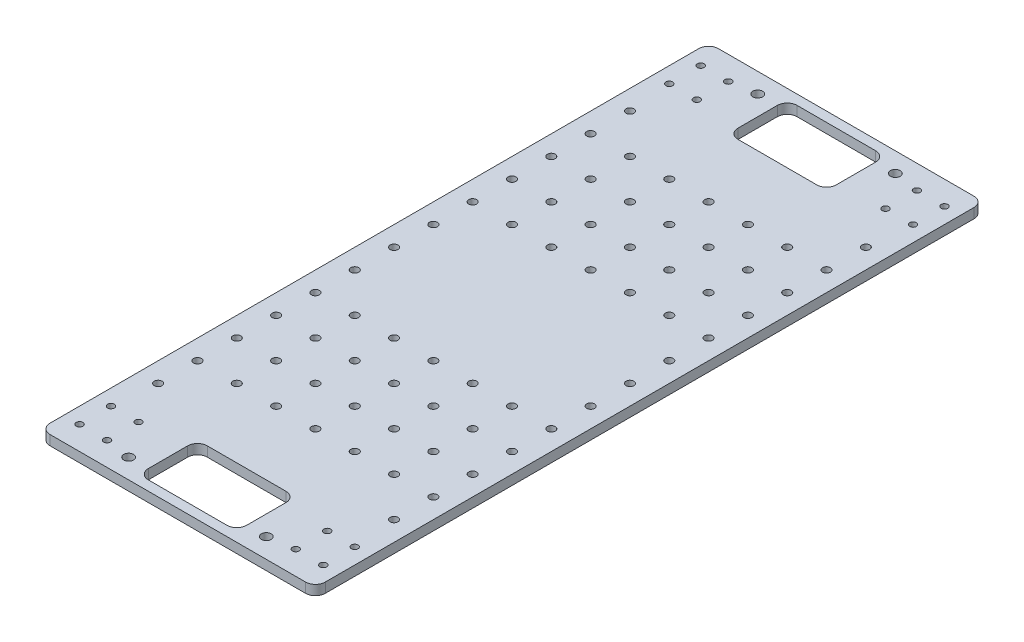
SolidWorks part; units mm, degrees
ref_plane "前视基准面" through (0, 0, 0) normal (0, 0, 1) x (1, 0, 0)
ref_plane "上视基准面" through (0, 0, 0) normal (0, 1, 0) x (1, 0, 0)
ref_plane "右视基准面" through (0, 0, 0) normal (1, 0, 0) x (0, 0, -1)
other "Configuration Table"
sketch "草图1" plane through (0, 0, 0) normal (0, 1, 0) x (1, 0, 0)
  line L0 (-1000, 0) -> (49000, 0)
  line L5 (-100, -170) -> (100, 170) construction
  line L6 (-100, 170) -> (100, -170) construction
  line L11 (0, -1000) -> (0, 49000) construction
  line L12 (-70, 0) -> (-60, 0)
  line L13 (-65, -170) -> (65, -170)
  line L14 (-70, 137) -> (-70, 130)
  line L15 (-70, 163) -> (-40, 163)
  line L16 (-40, 163) -> (-40, 137)
  line L17 (-40, 137) -> (-70, 137)
  line L18 (-70, -165) -> (-70, 165)
  line L19 (-70, 137) -> (-70, 142)
  line L20 (-40, 137) -> (-48, 137)
  line L21 (-48, 137) -> (-48, 142)
  line L22 (-48, 142) -> (-40, 142)
  line L23 (-70, 142) -> (-62, 142)
  line L24 (-62, 142) -> (-62, 137)
  line L25 (-70, 150) -> (-40, 150) construction
  line L28 (-70, 130) -> (0, 130)
  line L29 (-65, 170) -> (65, 170)
  line L30 (70, 165) -> (70, 130)
  line L31 (70, -165) -> (70, 170)
  line L32 (70, -170) -> (70, -130)
  line L33 (-70, -170) -> (-70, -130)
  line L34 (-20, 165) -> (20, 165)
  line L35 (0, 170) -> (0, 150)
  line L36 (-25, 160) -> (-25, 140)
  line L37 (-25, 150) -> (-25, 165)
  line L38 (-25, 150) -> (-25, 135)
  line L43 (25, 150) -> (25, 140)
  line L46 (25, 150) -> (25, 160)
  line L48 (25, -150) -> (25, -140)
  line L49 (25, -150) -> (25, -160)
  line L52 (-25, -150) -> (-25, -160)
  line L53 (-25, -150) -> (-25, -140)
  line L58 (0, 170) -> (0, 150)
  line L59 (0, 170) -> (0, 160)
  line L60 (-20, 135) -> (20, 135)
  line L61 (25, 165) -> (25, 135)
  line L62 (-20, -135) -> (20, -135)
  line L63 (-25, -135) -> (-25, -165)
  line L64 (-20, -165) -> (20, -165)
  line L65 (25, -135) -> (25, -165)
  circle A0 centre (-62, 142) radius 1.7
  circle A1 centre (-48, 142) radius 1.7
  circle A2 centre (-48, 158) radius 1.7
  circle A3 centre (-62, 158) radius 1.7
  circle A4 centre (48, 158) radius 1.7
  circle A5 centre (48, 142) radius 1.7
  circle A6 centre (62, 142) radius 1.7
  circle A7 centre (62, 158) radius 1.7
  circle A8 centre (62, -158) radius 1.7
  circle A9 centre (62, -142) radius 1.7
  circle A10 centre (48, -142) radius 1.7
  circle A11 centre (48, -158) radius 1.7
  circle A12 centre (-48, -142) radius 1.7
  circle A13 centre (-62, -142) radius 1.7
  circle A14 centre (-48, -158) radius 1.7
  circle A15 centre (-62, -158) radius 1.7
  circle A23 centre (35, 160) radius 2.5
  circle A24 centre (-60, 0) radius 2
  circle A27 centre (-60, 20) radius 2
  circle A28 centre (-40, 40) radius 2
  circle A29 centre (-60, 40) radius 2
  circle A30 centre (-40, 60) radius 2
  circle A31 centre (-60, 60) radius 2
  circle A32 centre (-40, 80) radius 2
  circle A33 centre (-60, 80) radius 2
  circle A34 centre (-40, 100) radius 2
  circle A35 centre (-60, 100) radius 2
  circle A37 centre (-60, 120) radius 2
  circle A40 centre (-20, 40) radius 2
  circle A41 centre (-40, 40) radius 2
  circle A42 centre (-20, 60) radius 2
  circle A43 centre (-40, 60) radius 2
  circle A44 centre (-20, 80) radius 2
  circle A45 centre (-40, 80) radius 2
  circle A46 centre (-20, 100) radius 2
  circle A47 centre (-40, 100) radius 2
  circle A52 centre (0, 40) radius 2
  circle A53 centre (-20, 40) radius 2
  circle A54 centre (0, 60) radius 2
  circle A55 centre (-20, 60) radius 2
  circle A56 centre (0, 80) radius 2
  circle A57 centre (-20, 80) radius 2
  circle A58 centre (0, 100) radius 2
  circle A59 centre (-20, 100) radius 2
  circle A64 centre (20, 40) radius 2
  circle A65 centre (0, 40) radius 2
  circle A66 centre (20, 60) radius 2
  circle A67 centre (0, 60) radius 2
  circle A68 centre (20, 80) radius 2
  circle A69 centre (0, 80) radius 2
  circle A70 centre (20, 100) radius 2
  circle A71 centre (0, 100) radius 2
  circle A76 centre (40, 40) radius 2
  circle A77 centre (20, 40) radius 2
  circle A78 centre (40, 60) radius 2
  circle A79 centre (20, 60) radius 2
  circle A80 centre (40, 80) radius 2
  circle A81 centre (20, 80) radius 2
  circle A82 centre (40, 100) radius 2
  circle A83 centre (20, 100) radius 2
  circle A86 centre (60, 20) radius 2
  circle A88 centre (60, 40) radius 2
  circle A89 centre (40, 40) radius 2
  circle A90 centre (60, 60) radius 2
  circle A91 centre (40, 60) radius 2
  circle A92 centre (60, 80) radius 2
  circle A93 centre (40, 80) radius 2
  circle A94 centre (60, 100) radius 2
  circle A95 centre (40, 100) radius 2
  circle A96 centre (60, 120) radius 2
  circle A98 centre (-35, 160) radius 2.5
  circle A99 centre (-40, 120) radius 2 [skipped]
  circle A100 centre (-20, 120) radius 2 [skipped]
  circle A101 centre (0, 120) radius 2 [skipped]
  circle A102 centre (20, 120) radius 2 [skipped]
  circle A103 centre (40, 120) radius 2 [skipped]
  circle A104 centre (-40, 20) radius 2 [skipped]
  circle A105 centre (-20, 20) radius 2 [skipped]
  circle A106 centre (0, 20) radius 2 [skipped]
  circle A107 centre (20, 20) radius 2 [skipped]
  circle A108 centre (40, 20) radius 2 [skipped]
  circle A109 centre (60, 0) radius 2
  circle A110 centre (60, -120) radius 2
  circle A111 centre (40, -100) radius 2
  circle A112 centre (60, -100) radius 2
  circle A113 centre (40, -80) radius 2
  circle A114 centre (60, -80) radius 2
  circle A115 centre (40, -60) radius 2
  circle A116 centre (60, -60) radius 2
  circle A117 centre (40, -40) radius 2
  circle A118 centre (60, -40) radius 2
  circle A119 centre (60, -20) radius 2
  circle A120 centre (20, -100) radius 2
  circle A121 centre (40, -100) radius 2
  circle A122 centre (20, -80) radius 2
  circle A123 centre (40, -80) radius 2
  circle A124 centre (20, -60) radius 2
  circle A125 centre (40, -60) radius 2
  circle A126 centre (20, -40) radius 2
  circle A127 centre (40, -40) radius 2
  circle A128 centre (0, -100) radius 2
  circle A129 centre (20, -100) radius 2
  circle A130 centre (0, -80) radius 2
  circle A131 centre (20, -80) radius 2
  circle A132 centre (0, -60) radius 2
  circle A133 centre (20, -60) radius 2
  circle A134 centre (0, -40) radius 2
  circle A135 centre (20, -40) radius 2
  circle A136 centre (-20, -100) radius 2
  circle A137 centre (0, -100) radius 2
  circle A138 centre (-20, -80) radius 2
  circle A139 centre (0, -80) radius 2
  circle A140 centre (-20, -60) radius 2
  circle A141 centre (0, -60) radius 2
  circle A142 centre (-20, -40) radius 2
  circle A143 centre (0, -40) radius 2
  circle A144 centre (-40, -100) radius 2
  circle A145 centre (-20, -100) radius 2
  circle A146 centre (-40, -80) radius 2
  circle A147 centre (-20, -80) radius 2
  circle A148 centre (-40, -60) radius 2
  circle A149 centre (-20, -60) radius 2
  circle A150 centre (-40, -40) radius 2
  circle A151 centre (-20, -40) radius 2
  circle A152 centre (-60, -120) radius 2
  circle A153 centre (-60, -100) radius 2
  circle A154 centre (-40, -100) radius 2
  circle A155 centre (-60, -80) radius 2
  circle A156 centre (-40, -80) radius 2
  circle A157 centre (-60, -60) radius 2
  circle A158 centre (-40, -60) radius 2
  circle A159 centre (-60, -40) radius 2
  circle A160 centre (-40, -40) radius 2
  circle A161 centre (-60, -20) radius 2
  arc A162 (70, -165) -> (65, -170) centre (65, -165) cw
  arc A163 (20, -165) -> (25, -160) centre (20, -160) ccw
  arc A164 (25, -140) -> (20, -135) centre (20, -140) ccw
  arc A165 (-20, -135) -> (-25, -140) centre (-20, -140) ccw
  arc A166 (-20, -165) -> (-25, -160) centre (-20, -160) cw
  arc A167 (-65, -170) -> (-70, -165) centre (-65, -165) cw
  arc A168 (20, 165) -> (25, 160) centre (20, 160) cw
  arc A169 (20, 135) -> (25, 140) centre (20, 140) ccw
  arc A170 (-25, 140) -> (-20, 135) centre (-20, 140) ccw
  arc A171 (-25, 160) -> (-20, 165) centre (-20, 160) cw
  arc A172 (70, 165) -> (65, 170) centre (65, 165) ccw
  arc A173 (-70, 165) -> (-65, 170) centre (-65, 165) cw
  circle A174 centre (35, -160) radius 2.5
  circle A175 centre (-35, -160) radius 2.5
  dimension "D12" = 3.4
  dimension "D13" = 3.4
  dimension "D3" = 10
  dimension "D4" = 4
  dimension "D8" = 7
  dimension "D5" = 5
  dimension "D1" = 200
  dimension "D2" = 340
  dimension "D6" = 7
  dimension "D7" = 30
  dimension "D9" = 5
  dimension "D10" = 8
  dimension "D11" = 8
  dimension "D14" = 25
  dimension "D16" = 15
  dimension "D21" = 20
  dimension "D22" = 10
extrude "凸台-拉伸2" add sketch "草图1" along normal blind 5
